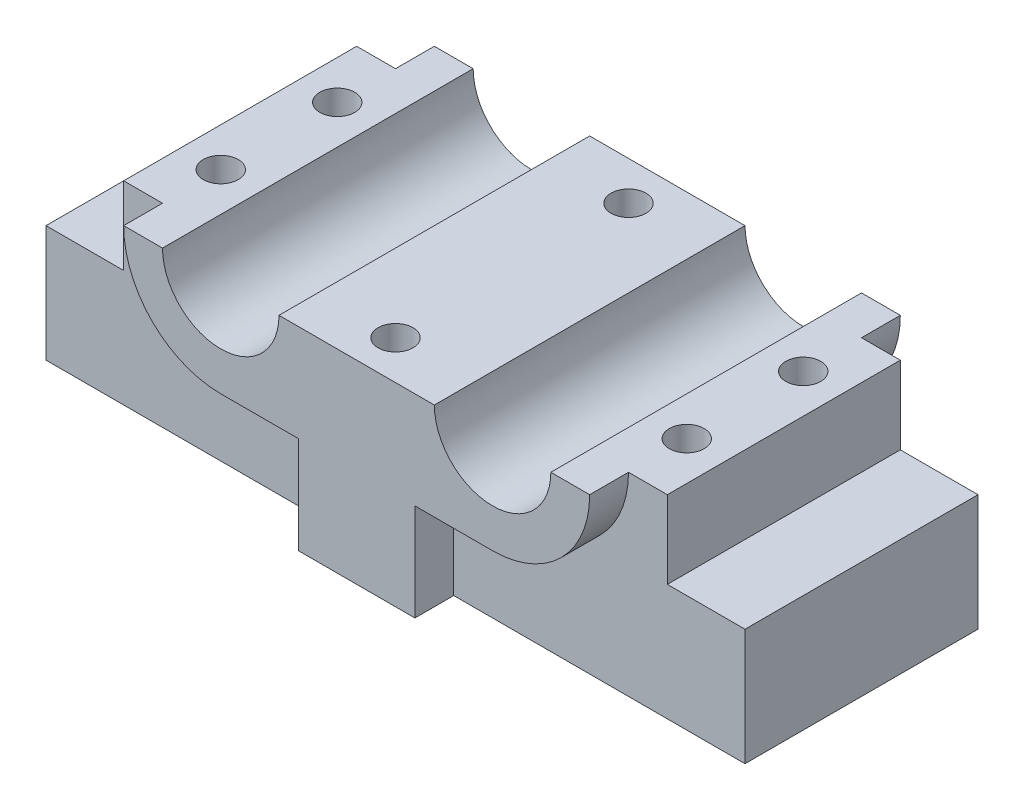
SolidWorks part; units mm, degrees
ref_plane "Front Plane" through (0, 0, 0) normal (0, 0, 1) x (1, 0, 0)
ref_plane "Top Plane" through (0, 0, 0) normal (0, 1, 0) x (1, 0, 0)
ref_plane "Right Plane" through (0, 0, 0) normal (1, 0, 0) x (0, 0, -1)
sketch "Sketch1" plane through (0, 0, 0) normal (0, 0, 1) x (1, 0, 0)
  line L1 (-45, 12.5) -> (45, 12.5)
  line L2 (-45, 12.5) -> (-45, -12.5)
  line L3 (-45, -12.5) -> (45, -12.5)
  line L4 (45, 12.5) -> (45, -12.5)
  line L5 (-45, 12.5) -> (45, -12.5) construction
  line L6 (-45, -12.5) -> (45, 12.5) construction
  point P0 (0, 0)
  dimension "D1" = 90
  dimension "D2" = 25
extrude "Boss-Extrude1" add sketch "Sketch1" along normal mid plane 40
sketch "Sketch2" plane through (0, 0, 20) normal (0, 0, 1) x (1, 0, 0)
  line L0 (45, 12.5) -> (-45, 12.5) construction
  line L1 (45, 12.5) -> (35, 12.5)
  line L2 (45, 12.5) -> (45, 2.5)
  line L3 (45, 2.5) -> (35, 2.5)
  line L4 (35, 12.5) -> (35, 2.5)
  line L5 (-35, 12.5) -> (-45, 12.5)
  line L6 (-35, 12.5) -> (-35, 2.5)
  line L7 (-35, 2.5) -> (-45, 2.5)
  line L8 (-45, 12.5) -> (-45, 2.5)
  line L9 (-45, 12.5) -> (-45, -12.5) construction
  dimension "D1" = 10
  dimension "D2" = 10
  dimension "D3" = 10
extrude "Cut-Extrude1" cut sketch "Sketch2" against normal blind 40
sketch "Sketch3" plane through (0, 0, 20) normal (0, 0, 1) x (1, 0, 0)
  line L0 (35, 12.5) -> (-35, 12.5) construction
  line L1 (17.5, 0) -> (7.5, 0)
  line L2 (7.5, 0) -> (7.5, -12.5)
  line L3 (-45, -12.5) -> (45, -12.5) construction
  line L4 (7.5, -12.5) -> (45, -12.5)
  line L5 (45, -12.5) -> (45, 2.5)
  line L6 (45, 2.5) -> (35, 2.5)
  line L7 (35, 2.5) -> (35, 12.5)
  line L8 (35, 12.5) -> (35, 2.5) construction
  line L9 (35, 12.5) -> (30, 12.5)
  line L10 (0, -13.75) -> (0, 13.75) construction
  line L11 (-35, 2.5) -> (-35, 12.5)
  line L12 (-45, 2.5) -> (-35, 2.5)
  line L13 (-45, -12.5) -> (-45, 2.5)
  line L14 (-7.5, -12.5) -> (-45, -12.5)
  line L15 (-7.5, 0) -> (-7.5, -12.5)
  line L16 (-17.5, 0) -> (-7.5, 0)
  line L17 (-35, 12.5) -> (-30, 12.5)
  arc A0 (30, 12.5) -> (17.5, 0) centre (17.5, 12.5) cw
  arc A1 (-30, 12.5) -> (-17.5, 0) centre (-17.5, 12.5) ccw
  dimension "D2" = 12.5
  dimension "D1" = 17.5
  dimension "D3" = 7.5
extrude "Cut-Extrude2" cut sketch "Sketch3" against normal blind 5
mirror "Mirror1" about plane through (0, 0, 0) normal (0, 0, 1) of "Cut-Extrude2"
sketch "Sketch4" plane through (0, 0, 20) normal (0, 0, 1) x (1, 0, 0)
  line L0 (30, 12.5) -> (-30, 12.5) construction
  line L1 (-25, 12.5) -> (-10, 12.5)
  line L2 (10, 12.5) -> (25, 12.5)
  arc A0 (25, 12.5) -> (10, 12.5) centre (17.5, 12.5) cw
  arc A1 (-25, 12.5) -> (-10, 12.5) centre (-17.5, 12.5) ccw
  dimension "D1" = 7.5
extrude "Cut-Extrude3" cut sketch "Sketch4" against normal up to next
hole_wizard "Hole1" positions "Sketch5" profile "Sketch6" legacy end condition through all
sketch "Sketch5" plane through (0, 12.5, 0) normal (0, 1, 0) x (1, 0, 0)
  point P0 (30, -7.5)
  dimension "D1" = 7.5
  dimension "D2" = 30
sketch "Sketch6" plane through (30, 12.5, 7.5) normal (1, 0, 0) x (0, 0, 1)
  line L0 (0, 0) -> (0, 25)
  line L1 (0, 25) -> (2.25, 25)
  line L2 (2.25, 25) -> (2.25, 0)
  line L3 (2.25, 0) -> (0, 0)
  line L4 (0, 110) -> (0, -10) construction
  dimension "Diameter" = 4.5
  dimension "Depth" = 25
pattern_linear "LPattern1" count 2 spacing 60 along (-1, 0, 0) count 2 spacing 15 along (0, 0, -1) of "Hole1"
hole_wizard "Hole2" positions "Sketch7" profile "Sketch8" legacy end condition through all
sketch "Sketch7" plane through (0, 12.5, 0) normal (0, 1, 0) x (1, 0, 0)
  point P0 (0, -15)
  dimension "D1" = 15
sketch "Sketch8" plane through (0, 12.5, 15) normal (1, 0, 0) x (0, 0, 1)
  line L0 (0, 0) -> (0, 25)
  line L1 (0, 25) -> (2.25, 25)
  line L2 (2.25, 25) -> (2.25, 0)
  line L3 (2.25, 0) -> (0, 0)
  line L4 (0, 110) -> (0, -10) construction
  dimension "Diameter" = 4.5
  dimension "Depth" = 25
mirror "Mirror2" about plane through (0, 0, 0) normal (0, 0, 1) of "Hole2"
